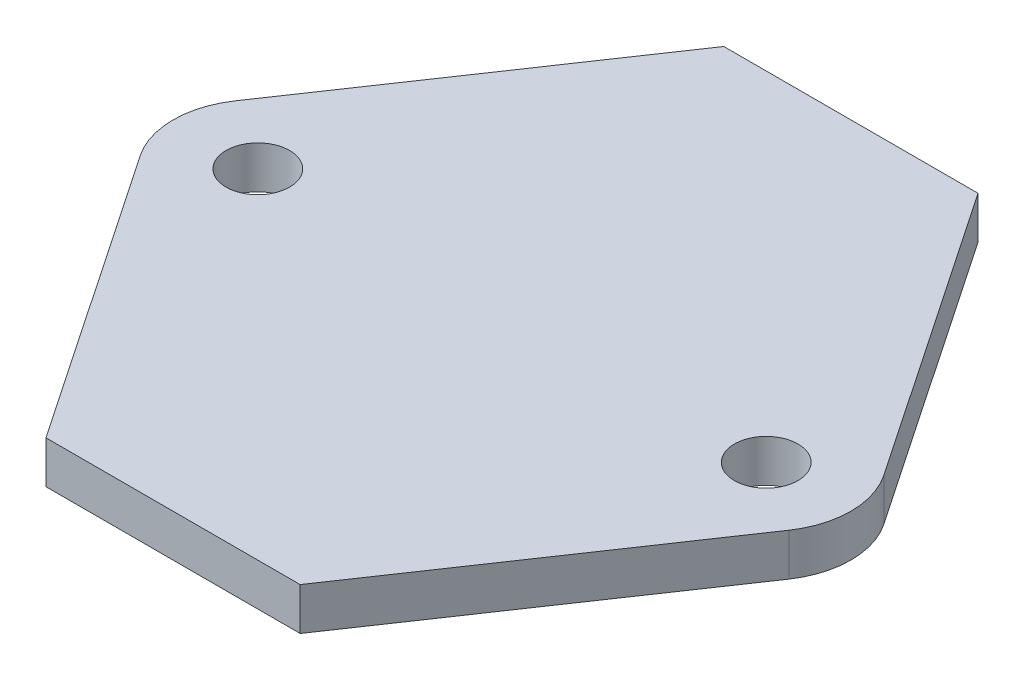
SolidWorks part; units mm, degrees
material "AISI 4340 Steel, normalized"
ref_plane "Front Plane" through (0, 0, 0) normal (0, 0, 1) x (1, 0, 0)
ref_plane "Top Plane" through (0, 0, 0) normal (0, 1, 0) x (1, 0, 0)
ref_plane "Right Plane" through (0, 0, 0) normal (1, 0, 0) x (0, 0, -1)
sketch "Sketch1" plane through (0, 0, 0) normal (0, 1, 0) x (1, 0, 0)
  line L0 (9.525, -25.4) -> (24.3086, -3.5595)
  line L1 (-9.525, 25.4) -> (9.525, 25.4)
  line L2 (-9.525, 25.4) -> (-9.525, -25.4)
  line L3 (-9.525, -25.4) -> (9.525, -25.4)
  line L4 (9.525, 25.4) -> (9.525, -25.4)
  line L5 (-9.525, 25.4) -> (9.525, -25.4) construction
  line L6 (-9.525, -25.4) -> (9.525, 25.4) construction
  line L7 (24.3086, 3.5595) -> (9.525, 25.4)
  line L8 (0, 0) -> (0, 14.7529) construction
  line L9 (-24.3086, 3.5595) -> (-9.525, 25.4)
  line L10 (-9.525, -25.4) -> (-24.3086, -3.5595)
  line L11 (19.05, 0) -> (0, 0) construction
  circle A0 centre (19.05, 0) radius 6.35
  circle A1 centre (-19.05, 0) radius 6.35
  point P0 (0, 0)
  dimension "D3" = 12.7
  dimension "D1" = 19.05
  dimension "D2" = 50.8
  dimension "D4" = 19.05
extrude "Boss-Extrude1" add sketch "Sketch1" along normal mid plane 3.175 contours L4 L1 L2 L3 | A0 L4 L0 | A0 | A0 L7 L4 | L9 A1 L2 | A1 | L2 A1 L10
sketch "Sketch2" plane through (0, 1.5875, 0) normal (0, 1, 0) x (1, 0, 0)
  line L6 (9.525, -25.4) -> (24.3086, -3.5595)
  line L7 (24.3086, 3.5595) -> (9.525, 25.4)
  line L8 (9.525, 25.4) -> (-9.525, 25.4)
  line L9 (-9.525, 25.4) -> (-24.3086, 3.5595)
  line L10 (-24.3086, -3.5595) -> (-9.525, -25.4)
  line L11 (-9.525, -25.4) -> (9.525, -25.4)
  line L12 (9.525, -25.4) -> (24.3086, -3.5595)
  line L13 (24.3086, 3.5595) -> (9.525, 25.4)
  line L14 (9.525, 25.4) -> (-9.525, 25.4)
  line L15 (-9.525, 25.4) -> (-24.3086, 3.5595)
  line L16 (-24.3086, -3.5595) -> (-9.525, -25.4)
  line L17 (-9.525, -25.4) -> (9.525, -25.4)
  arc A2 (24.3086, -3.5595) -> (24.3086, 3.5595) centre (19.05, 0) ccw
  arc A3 (-24.3086, 3.5595) -> (-24.3086, -3.5595) centre (-19.05, 0) ccw
  arc A4 (24.3086, -3.5595) -> (24.3086, 3.5595) centre (19.05, 0) ccw
  arc A5 (-24.3086, 3.5595) -> (-24.3086, -3.5595) centre (-19.05, 0) ccw
  point P2 (-19.05, 0)
  point P7 (19.05, 0)
  dimension "D1" = 0
hole_wizard "3/16 (0.1875) Diameter Hole1" positions "3DSketch1" profile "Sketch3" hole size "3/16" standard "ANSI Inch" end condition through all
sketch3d "3DSketch1"
  point P0 (19.05, 1.5875, 0)
  point P3 (-19.05, 1.5875, 0)
sketch "Sketch3" plane through (19.05, 1.5875, 0) normal (1, 0, 0) x (0, 0, 1)
  line L0 (0, 0) -> (0, 3.175)
  line L1 (0, 3.175) -> (2.3812, 3.175)
  line L2 (2.3812, 3.175) -> (2.3812, 0)
  line L5 (2.3812, 0) -> (0, 0)
  line L11 (0, -6.35) -> (0, 107.95) construction
  dimension "Thru Hole Dia." = 4.7625
  dimension "Thru Hole Depth" = 3.175
